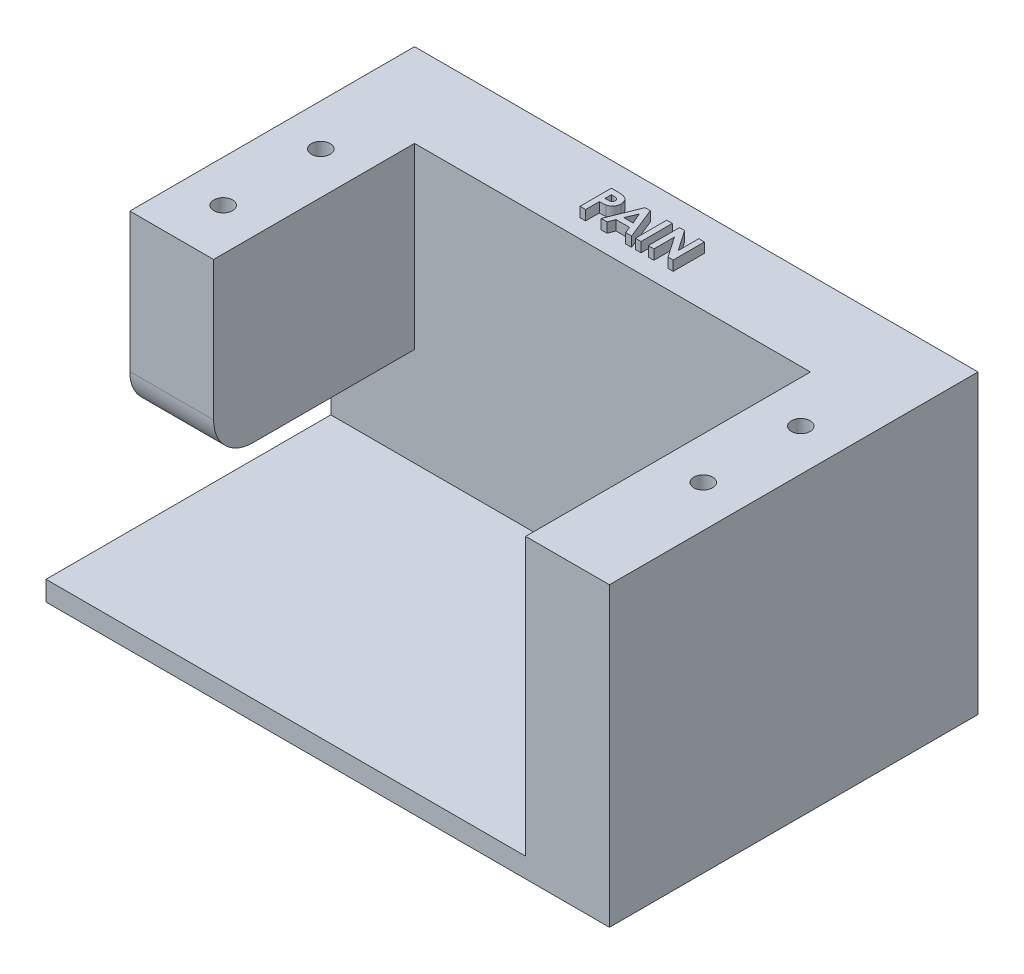
SolidWorks part; units mm, degrees
ref_plane "Front Plane" through (0, 0, 0) normal (0, 0, 1) x (1, 0, 0)
ref_plane "Top Plane" through (0, 0, 0) normal (0, 1, 0) x (1, 0, 0)
ref_plane "Right Plane" through (0, 0, 0) normal (1, 0, 0) x (0, 0, -1)
sketch "Sketch1" plane through (0, 0, 0) normal (0, 1, 0) x (1, 0, 0)
  line L0 (-28.58, -18.695) -> (28.58, -18.695)
  line L1 (-20.08, -10.195) -> (20.08, -10.195)
  line L2 (-20.08, -10.195) -> (-20.08, 10.195)
  line L3 (-20.08, 10.195) -> (20.08, 10.195)
  line L4 (20.08, -10.195) -> (20.08, 10.195)
  line L5 (-20.08, -10.195) -> (20.08, 10.195) construction
  line L6 (-20.08, 10.195) -> (20.08, -10.195) construction
  line L7 (28.58, -18.695) -> (28.58, 18.695)
  line L8 (-28.58, 18.695) -> (28.58, 18.695)
  line L9 (-28.58, -18.695) -> (-28.58, 18.695)
  point P0 (0, 0)
  dimension "D1" = 40.16
  dimension "D2" = 20.39
  dimension "D3" = 8.5
extrude "Boss-Extrude1" add sketch "Sketch1" along normal blind 2 contours L1 L4 L3 L2 | L9 L0 L7 L8 L4 L1 L2 L3
sketch "Sketch2" plane through (0, 2, 0) normal (0, 1, 0) x (1, 0, 0)
  line L4 (-20.08, -10.195) -> (20.08, -10.195)
  line L5 (20.08, -10.195) -> (20.08, 10.195)
  line L6 (20.08, 10.195) -> (-20.08, 10.195)
  line L7 (-20.08, 10.195) -> (-20.08, -10.195)
  line L8 (-20.08, -10.195) -> (20.08, -10.195)
  line L9 (20.08, -10.195) -> (20.08, 10.195)
  line L10 (20.08, 10.195) -> (-20.08, 10.195)
  line L11 (-20.08, 10.195) -> (-20.08, -10.195)
  line L12 (-28.58, -18.695) -> (28.58, -18.695)
  line L13 (28.58, -18.695) -> (28.58, 18.695)
  line L14 (28.58, 18.695) -> (-28.58, 18.695)
  line L15 (-28.58, 18.695) -> (-28.58, -18.695)
  line L16 (-28.58, -18.695) -> (28.58, -18.695) construction
  line L17 (28.58, -18.695) -> (28.58, 18.695) construction
  line L18 (28.58, 18.695) -> (-28.58, 18.695) construction
  line L19 (-28.58, 18.695) -> (-28.58, -18.695) construction
  line M9 (-28.58, 18.695) -> (-28.58, -18.695)
  line M10 (-28.58, -18.695) -> (28.58, -18.695)
  line M11 (28.58, -18.695) -> (28.58, 18.695)
  line M12 (28.58, 18.695) -> (-28.58, 18.695)
  dimension "D1" = 0
  dimension "D2" = 0
extrude "Boss-Extrude2" add sketch "Sketch2" along normal blind 28.1 contours L11 L10 L9 L8 M12 M9 M10 M11
sketch "Sketch3" plane through (0, 30.1, 0) normal (0, 1, 0) x (1, 0, 0)
  line L1 (20.08, -10.195) -> (-28.58, -10.195)
  line L2 (20.08, -10.195) -> (20.08, -18.695)
  line L3 (20.08, -18.695) -> (-28.58, -18.695)
  line L4 (-28.58, -10.195) -> (-28.58, -18.695)
extrude "Cut-Extrude1" cut sketch "Sketch3" against normal up to surface (28.1 mm away) up to face at (0, 2, 0)
sketch "Sketch5" plane through (-20.08, 0, 0) normal (1, 0, 0) x (0, 0, -1)
  line L0 (-10.195, 30.1) -> (-10.195, 2) construction
  line L1 (10.195, 2) -> (-10.195, 2)
  line L2 (10.195, 2) -> (10.195, 12)
  line L3 (10.195, 12) -> (-10.195, 12)
  line L4 (-10.195, 2) -> (-10.195, 12)
  dimension "D1" = 10
extrude "Cut-Extrude2" cut sketch "Sketch5" against normal up to next
fillet "Fillet1" radius 4 1 edges at (-24.33, 12, 10.195)
sketch "Sketch6" plane through (0, 30.1, 0) normal (0, 1, 0) x (1, 0, 0)
  line L0 (-1.9157, 0) -> (18.1643, 0) construction
  line L2 (0, 0) -> (0, 10.195) construction
  circle A0 centre (-24.35, -4.95) radius 2.25 construction
  circle A1 centre (-24.35, -4.95) radius 0.95
  circle A2 centre (-24.35, 4.95) radius 0.95
  circle A3 centre (24.35, 4.95) radius 0.95
  circle A4 centre (24.35, -4.95) radius 0.95
  dimension "D1" = 2.7
  dimension "D2" = 22.1
  dimension "D3" = 4.5
  dimension "D4" = 1.9
extrude "Cut-Extrude3" cut sketch "Sketch6" against normal blind 12
sketch "Sketch7" plane through (0, 30.1, 0) normal (0, 1, 0) x (1, 0, 0)
  text T0 "<b>PAIN</b>" font "Century Gothic" height 3.175
extrude "Boss-Extrude3" add sketch "Sketch7" along normal blind 1
